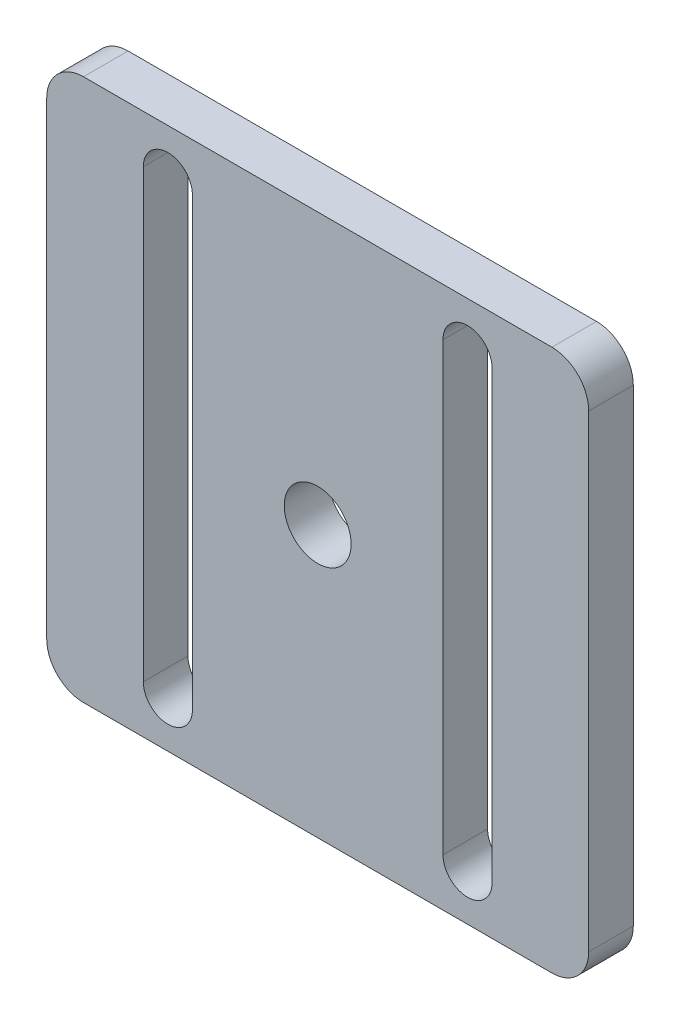
SolidWorks part; units mm, degrees
material "Thornel Mat VMA"
ref_plane "Alzado" through (0, 0, 0) normal (0, 0, 1) x (1, 0, 0)
ref_plane "Planta" through (0, 0, 0) normal (0, 1, 0) x (1, 0, 0)
ref_plane "Vista lateral" through (0, 0, 0) normal (1, 0, 0) x (0, 0, -1)
sketch "Croquis1" plane through (0, 0, 0) normal (0, 0, 1) x (1, 0, 0)
  line L8 (-117.3271, 45.8502) -> (-96.3271, 45.8502)
  line L9 (-94.3271, 47.8502) -> (-94.3271, 68.8502)
  line L10 (-96.3271, 70.8502) -> (-117.3271, 70.8502)
  line L11 (-114.6446, 68.3502) -> (-114.6446, 48.3502)
  line L12 (-112.4446, 48.3502) -> (-112.4446, 68.3502)
  line L13 (-119.3271, 68.8502) -> (-119.3271, 47.8502)
  line L14 (-99.0096, 48.3502) -> (-99.0096, 68.3502)
  line L15 (-101.2096, 68.3502) -> (-101.2096, 48.3502)
  arc A7 (-96.3271, 45.8502) -> (-94.3271, 47.8502) centre (-96.3271, 47.8502) ccw
  arc A8 (-94.3271, 68.8502) -> (-96.3271, 70.8502) centre (-96.3271, 68.8502) ccw
  arc A9 (-114.6446, 48.3502) -> (-112.4446, 48.3502) centre (-113.5446, 48.3502) ccw
  arc A10 (-112.4446, 68.3502) -> (-114.6446, 68.3502) centre (-113.5446, 68.3502) ccw
  arc A11 (-117.3271, 45.8502) -> (-119.3271, 47.8502) centre (-117.3271, 47.8502) cw
  arc A12 (-101.2096, 48.3502) -> (-99.0096, 48.3502) centre (-100.1096, 48.3502) ccw
  arc A13 (-99.0096, 68.3502) -> (-101.2096, 68.3502) centre (-100.1096, 68.3502) ccw
  circle A14 centre (-106.8271, 58.3502) radius 1.5
  arc A15 (-117.3271, 70.8502) -> (-119.3271, 68.8502) centre (-117.3271, 68.8502) ccw
  dimension "D1" = 2
extrude "Saliente-Extruir1" add sketch "Croquis1" along normal blind 2
sketch "Croquis2" plane through (0, 0, 2) normal (0, 0, 1) x (1, 0, 0)
  line L8 (-96.3271, 70.8502) -> (-117.3271, 70.8502)
  line L9 (-119.3271, 68.8502) -> (-119.3271, 47.8502)
  line L10 (-117.3271, 45.8502) -> (-96.3271, 45.8502)
  line L11 (-94.3271, 47.8502) -> (-94.3271, 68.8502)
  line L12 (-96.3271, 70.8502) -> (-117.3271, 70.8502)
  line L13 (-119.3271, 68.8502) -> (-119.3271, 47.8502)
  line L14 (-117.3271, 45.8502) -> (-96.3271, 45.8502)
  line L15 (-94.3271, 47.8502) -> (-94.3271, 68.8502)
  line L20 (-96.3271, 70.5002) -> (-117.3271, 70.5002)
  line L21 (-118.9771, 68.8502) -> (-118.9771, 47.8502)
  line L22 (-117.3271, 46.2002) -> (-96.3271, 46.2002)
  line L23 (-94.6771, 47.8502) -> (-94.6771, 68.8502)
  line L24 (-96.3271, 70.5002) -> (-117.3271, 70.5002)
  line L25 (-118.9771, 68.8502) -> (-118.9771, 47.8502)
  line L26 (-117.3271, 46.2002) -> (-96.3271, 46.2002)
  line L27 (-94.6771, 47.8502) -> (-94.6771, 68.8502)
  arc A8 (-94.3271, 68.8502) -> (-96.3271, 70.8502) centre (-96.3271, 68.8502) ccw
  arc A9 (-117.3271, 70.8502) -> (-119.3271, 68.8502) centre (-117.3271, 68.8502) ccw
  arc A10 (-119.3271, 47.8502) -> (-117.3271, 45.8502) centre (-117.3271, 47.8502) ccw
  arc A11 (-96.3271, 45.8502) -> (-94.3271, 47.8502) centre (-96.3271, 47.8502) ccw
  arc A12 (-94.3271, 68.8502) -> (-96.3271, 70.8502) centre (-96.3271, 68.8502) ccw
  arc A13 (-117.3271, 70.8502) -> (-119.3271, 68.8502) centre (-117.3271, 68.8502) ccw
  arc A14 (-119.3271, 47.8502) -> (-117.3271, 45.8502) centre (-117.3271, 47.8502) ccw
  arc A15 (-96.3271, 45.8502) -> (-94.3271, 47.8502) centre (-96.3271, 47.8502) ccw
  arc A20 (-94.6771, 68.8502) -> (-96.3271, 70.5002) centre (-96.3271, 68.8502) ccw
  arc A21 (-117.3271, 70.5002) -> (-118.9771, 68.8502) centre (-117.3271, 68.8502) ccw
  arc A22 (-118.9771, 47.8502) -> (-117.3271, 46.2002) centre (-117.3271, 47.8502) ccw
  arc A23 (-96.3271, 46.2002) -> (-94.6771, 47.8502) centre (-96.3271, 47.8502) ccw
  arc A24 (-94.6771, 68.8502) -> (-96.3271, 70.5002) centre (-96.3271, 68.8502) ccw
  arc A25 (-117.3271, 70.5002) -> (-118.9771, 68.8502) centre (-117.3271, 68.8502) ccw
  arc A26 (-118.9771, 47.8502) -> (-117.3271, 46.2002) centre (-117.3271, 47.8502) ccw
  arc A27 (-96.3271, 46.2002) -> (-94.6771, 47.8502) centre (-96.3271, 47.8502) ccw
  dimension "D1" = 0
  dimension "D2" = 0.35
extrude "Cortar-Extruir1" cut sketch "Croquis2" against normal up to vertex (2 mm away)
